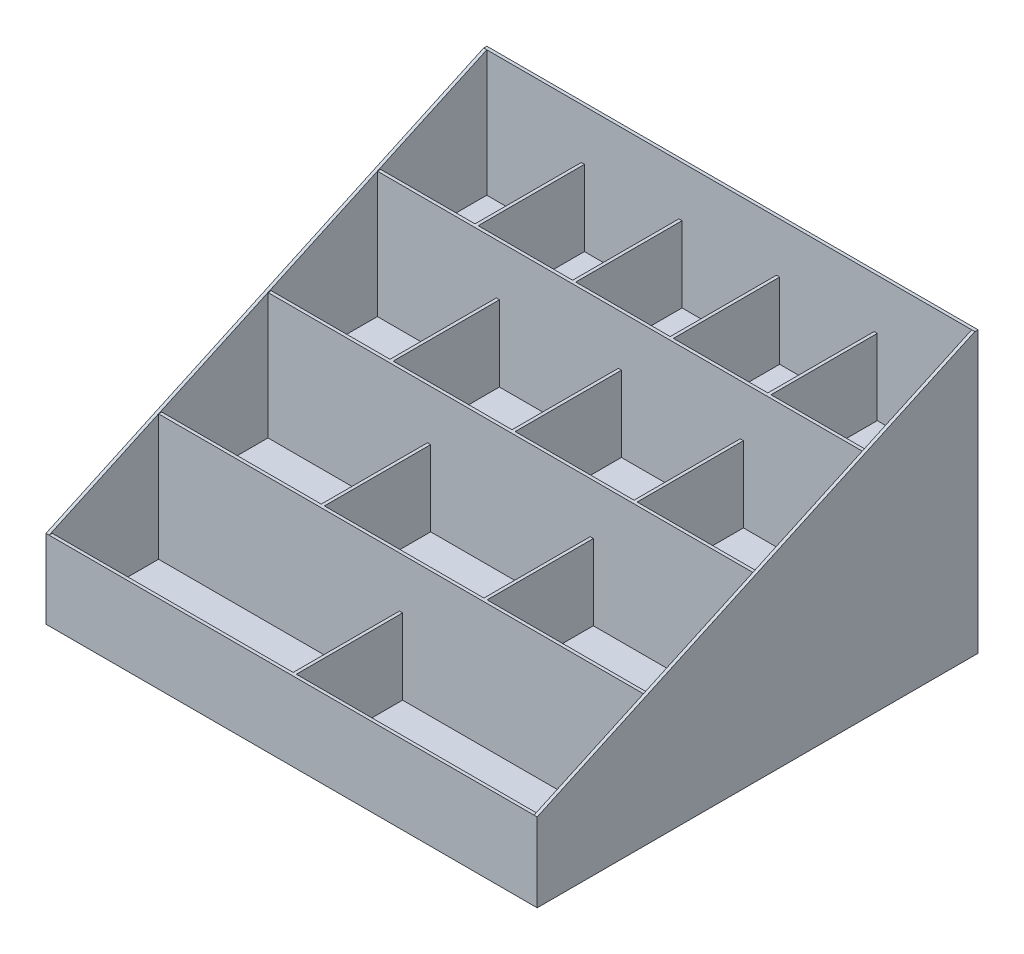
SolidWorks part; units mm, degrees
ref_plane "Front Plane" through (0, 0, 0) normal (0, 0, 1) x (1, 0, 0)
ref_plane "Top Plane" through (0, 0, 0) normal (0, 1, 0) x (1, 0, 0)
ref_plane "Right Plane" through (0, 0, 0) normal (1, 0, 0) x (0, 0, -1)
sketch "Sketch1" plane through (0, 0, 0) normal (1, 0, 0) x (0, 0, -1)
  line L1 (0, 0) -> (222.25, 0)
  line L3 (220.6625, 115.8875) -> (165.4969, 115.8875)
  line L4 (165.4969, 115.8875) -> (165.4969, 90.4875)
  line L5 (165.4969, 90.4875) -> (110.3313, 90.4875)
  line L6 (110.3313, 90.4875) -> (110.3313, 65.0875)
  line L7 (110.3313, 65.0875) -> (55.1656, 65.0875)
  line L8 (55.1656, 65.0875) -> (55.1656, 39.6875)
  line L9 (55.1656, 39.6875) -> (0, 39.6875)
  line L10 (0, 39.6875) -> (0, 14.2875)
  line L11 (0, 14.2875) -> (0, 0)
  line L13 (222.25, 115.8875) -> (222.25, 0)
  line L14 (220.6625, 115.8875) -> (220.6625, 141.2875)
  line L15 (220.6625, 141.2875) -> (222.25, 141.2875)
  line L16 (222.25, 141.2875) -> (222.25, 115.8875)
  dimension "D1" = 222.25
  dimension "D2" = 25.4
  dimension "D3" = 39.6875
  dimension "D4" = 1.5875
extrude "Boss-Extrude1" add sketch "Sketch1" along normal mid plane 247.65
sketch "Sketch3" plane through (0, 39.6875, 0) normal (0, 1, 0) x (1, 0, 0)
  line L0 (123.825, 55.1656) -> (-123.825, 55.1656) construction
  line L1 (-122.2375, 55.1656) -> (-0.7937, 55.1656)
  line L2 (-122.2375, 55.1656) -> (-122.2375, 1.5875)
  line L3 (-122.2375, 1.5875) -> (-0.7938, 1.5875)
  line L4 (-0.7937, 55.1656) -> (-0.7938, 1.5875)
  line L5 (-122.2375, 1.5875) -> (-123.825, 1.5875) construction
  line L6 (0.7938, 55.1656) -> (122.2375, 55.1656)
  line L7 (0.7938, 55.1656) -> (0.7937, 1.5875)
  line L8 (0.7937, 1.5875) -> (122.2375, 1.5875)
  line L9 (122.2375, 55.1656) -> (122.2375, 1.5875)
  line L10 (-123.825, 55.1656) -> (-123.825, 0) construction
  line L11 (-0.7938, 1.5875) -> (0.7937, 1.5875) construction
  line L12 (122.2375, 1.5875) -> (123.825, 1.5875) construction
  line L13 (123.825, 55.1656) -> (123.825, 0) construction
  line L14 (-122.2375, 1.5875) -> (-122.2375, 0) construction
  line L15 (123.825, 0) -> (-123.825, 0) construction
  dimension "D1" = 1.5875
extrude "Cut-Extrude1" cut sketch "Sketch3" against normal blind 38.1
sketch "Sketch4" plane through (0, 65.0875, 0) normal (0, 1, 0) x (1, 0, 0)
  line L0 (123.825, 110.3313) -> (-123.825, 110.3313) construction
  line L1 (-122.2375, 110.3313) -> (-41.8042, 110.3313)
  line L2 (-122.2375, 110.3313) -> (-122.2375, 56.7531)
  line L3 (-122.2375, 56.7531) -> (-41.8042, 56.7531)
  line L4 (-41.8042, 110.3313) -> (-41.8042, 56.7531)
  line L5 (-40.2167, 110.3313) -> (40.2167, 110.3313)
  line L6 (-40.2167, 110.3313) -> (-40.2167, 56.7531)
  line L7 (-40.2167, 56.7531) -> (40.2167, 56.7531)
  line L8 (40.2167, 110.3313) -> (40.2167, 56.7531)
  line L9 (41.8042, 110.3313) -> (122.2375, 110.3313)
  line L10 (41.8042, 110.3313) -> (41.8042, 56.7531)
  line L11 (41.8042, 56.7531) -> (122.2375, 56.7531)
  line L12 (122.2375, 110.3313) -> (122.2375, 56.7531)
  line L13 (-122.2375, 55.1656) -> (-122.2375, 1.5875) construction
  line L14 (122.2375, 1.5875) -> (122.2375, 55.1656) construction
  line L15 (-41.8042, 56.7531) -> (-40.2167, 56.7531) construction
  line L16 (0.7938, 55.1656) -> (-0.7937, 55.1656) construction
  dimension "D1" = 3
extrude "Cut-Extrude2" cut sketch "Sketch4" against normal blind 38.1
sketch "Sketch5" plane through (0, 90.4875, 0) normal (0, 1, 0) x (1, 0, 0)
  line L0 (60.7219, 111.9188) -> (62.3094, 111.9187) construction
  line L1 (-122.2375, 165.4969) -> (-62.3094, 165.4969)
  line L2 (-122.2375, 165.4969) -> (-122.2375, 111.9187)
  line L3 (-122.2375, 111.9187) -> (-62.3094, 111.9188)
  line L4 (-62.3094, 165.4969) -> (-62.3094, 111.9188)
  line L5 (123.825, 165.4969) -> (-123.825, 165.4969) construction
  line L6 (-122.2375, 110.3312) -> (-122.2375, 56.7531) construction
  line L8 (-60.7219, 165.4969) -> (-0.7937, 165.4969)
  line L9 (-60.7219, 165.4969) -> (-60.7219, 111.9187)
  line L10 (-60.7219, 111.9187) -> (-0.7937, 111.9188)
  line L11 (-0.7937, 165.4969) -> (-0.7937, 111.9188)
  line L12 (0.7938, 165.4969) -> (60.7219, 165.4969)
  line L13 (0.7938, 165.4969) -> (0.7938, 111.9187)
  line L14 (0.7938, 111.9187) -> (60.7219, 111.9188)
  line L15 (60.7219, 165.4969) -> (60.7219, 111.9188)
  line L16 (62.3094, 165.4969) -> (122.2375, 165.4969)
  line L17 (62.3094, 165.4969) -> (62.3094, 111.9187)
  line L18 (62.3094, 111.9187) -> (122.2375, 111.9188)
  line L19 (122.2375, 165.4969) -> (122.2375, 111.9188)
  line L25 (123.825, 110.3312) -> (122.2375, 110.3312) construction
  line L27 (122.2375, 111.9188) -> (122.2375, 110.3312) construction
  line L28 (123.825, 110.3312) -> (-123.825, 110.3312) construction
  line L30 (122.2375, 56.7531) -> (122.2375, 110.3312) construction
  dimension "D1" = 4
extrude "Cut-Extrude3" cut sketch "Sketch5" against normal blind 38.1
sketch "Sketch6" plane through (0, 115.8875, 0) normal (0, 1, 0) x (1, 0, 0)
  line L0 (123.825, 165.4969) -> (-123.825, 165.4969) construction
  line L1 (-122.2375, 220.6625) -> (-74.6125, 220.6625)
  line L2 (-122.2375, 220.6625) -> (-122.2375, 167.0844)
  line L3 (-122.2375, 167.0844) -> (-74.6125, 167.0844)
  line L4 (-74.6125, 220.6625) -> (-74.6125, 167.0844)
  line L6 (-122.2375, 167.0844) -> (-122.2375, 165.4969) construction
  line L8 (-122.2375, 165.4969) -> (-123.825, 165.4969) construction
  line L9 (-122.2375, 165.4969) -> (-122.2375, 111.9187) construction
  line L10 (-25.4, 220.6625) -> (-25.4, 167.0844)
  line L11 (-73.025, 220.6625) -> (-25.4, 220.6625)
  line L12 (-73.025, 220.6625) -> (-73.025, 167.0844)
  line L13 (-73.025, 167.0844) -> (-25.4, 167.0844)
  line L14 (23.8125, 220.6625) -> (23.8125, 167.0844)
  line L15 (-23.8125, 220.6625) -> (23.8125, 220.6625)
  line L16 (-23.8125, 220.6625) -> (-23.8125, 167.0844)
  line L17 (-23.8125, 167.0844) -> (23.8125, 167.0844)
  line L18 (73.025, 220.6625) -> (73.025, 167.0844)
  line L19 (25.4, 220.6625) -> (73.025, 220.6625)
  line L20 (25.4, 220.6625) -> (25.4, 167.0844)
  line L21 (25.4, 167.0844) -> (73.025, 167.0844)
  line L22 (122.2375, 220.6625) -> (122.2375, 167.0844)
  line L23 (74.6125, 220.6625) -> (122.2375, 220.6625)
  line L24 (74.6125, 220.6625) -> (74.6125, 167.0844)
  line L25 (74.6125, 167.0844) -> (122.2375, 167.0844)
  line L26 (122.2375, 220.6625) -> (123.825, 220.6625) construction
  line L28 (-74.6125, 220.6625) -> (-73.025, 220.6625) construction
  line L29 (123.825, 220.6625) -> (-123.825, 220.6625) construction
  line L30 (123.825, 220.6625) -> (123.825, 165.4969) construction
  dimension "D1" = 5
extrude "Cut-Extrude4" cut sketch "Sketch6" against normal blind 38.1
sketch "Sketch7" plane through (123.825, 0, 0) normal (1, 0, 0) x (0, 0, -1)
  line L0 (0, 39.6875) -> (220.6625, 141.2875)
  line L2 (220.6625, 141.2875) -> (220.6625, 39.6875)
  line L3 (220.6625, 39.6875) -> (0, 39.6875)
extrude "Boss-Extrude2" add sketch "Sketch7" against normal blind 1.5875
mirror "Mirror1" about plane through (0, 0, 0) normal (1, 0, 0) of "Boss-Extrude2"
sketch "Sketch8" plane through (123.825, 0, 0) normal (1, 0, 0) x (0, 0, -1)
  line L1 (100.7285, 3.175) -> (219.075, 3.175)
  line L2 (219.075, 3.175) -> (219.075, 74.6125)
  line L3 (219.075, 74.6125) -> (167.0844, 74.6125)
  line L5 (220.6625, 77.7875) -> (167.0844, 77.7875) construction
  line L7 (0, 0) -> (222.25, 0) construction
  line L8 (222.25, 0) -> (222.25, 141.2875) construction
  line L9 (167.0844, 74.6125) -> (167.0844, 49.6379)
  line L12 (167.0844, 49.6379) -> (100.7285, 3.175)
  dimension "D1" = 35
  dimension "D2" = 3.175
  dimension "D3" = 3.175
  dimension "D4" = 3.175
  dimension "D5" = 3.175
extrude "Cut-Extrude5" [suppressed] cut sketch "Sketch8" against normal through all
